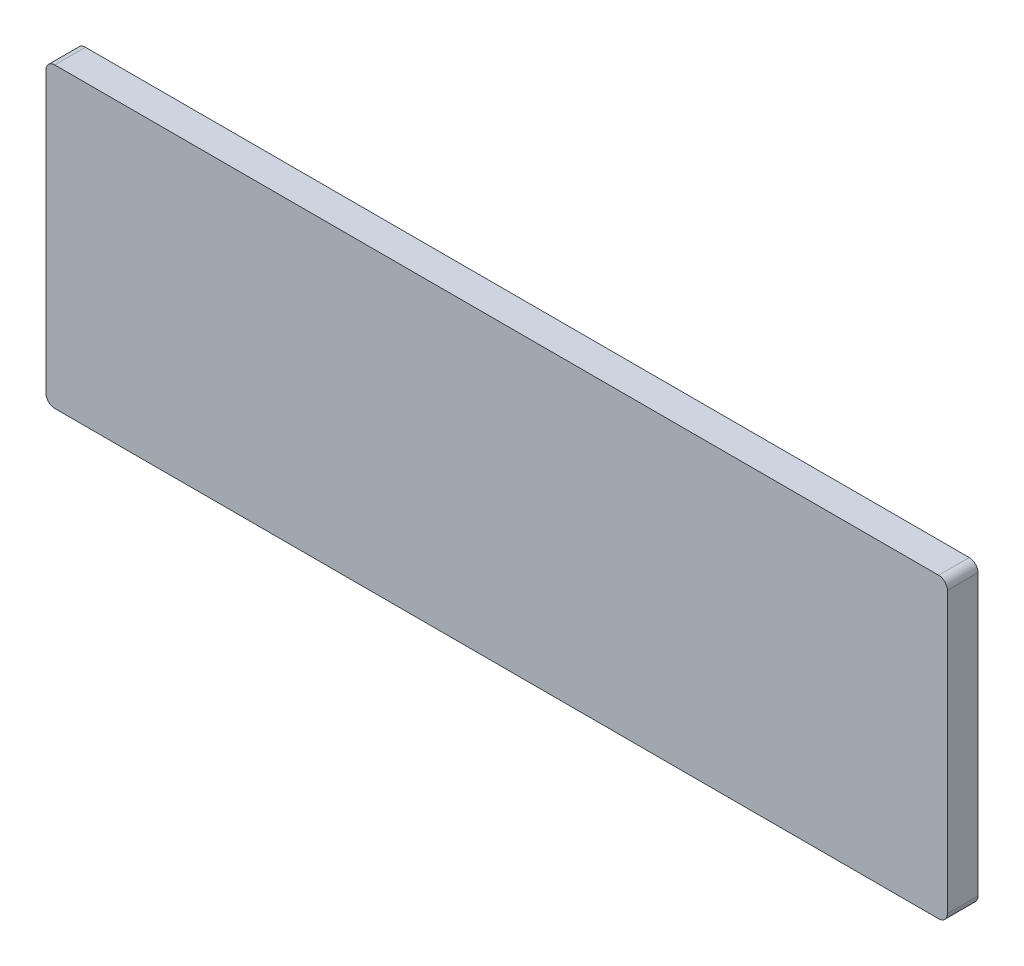
SolidWorks part; units mm, degrees
material "自定义塑料"
ref_plane "前视基准面" through (0, 0, 0) normal (0, 0, 1) x (1, 0, 0)
ref_plane "上视基准面" through (0, 0, 0) normal (0, 1, 0) x (1, 0, 0)
ref_plane "右视基准面" through (0, 0, 0) normal (1, 0, 0) x (0, 0, -1)
sketch "草图1" plane through (0, 0, 0) normal (0, 0, 1) x (1, 0, 0)
  line L0 (-103, 34) -> (103, -34) construction
  line L1 (-101, 34) -> (101, 34)
  line L2 (-103, 32) -> (-103, -32)
  line L3 (-101, -34) -> (101, -34)
  line L4 (103, 32) -> (103, -32)
  line L5 (103, 34) -> (-103, -34) construction
  arc A0 (101, -34) -> (103, -32) centre (101, -32) ccw
  arc A1 (101, 34) -> (103, 32) centre (101, 32) cw
  arc A2 (-103, -32) -> (-101, -34) centre (-101, -32) ccw
  arc A3 (-101, 34) -> (-103, 32) centre (-101, 32) ccw
  point P4 (0, 0)
  dimension "D3" = 2
  dimension "D1" = 206
  dimension "D2" = 68
extrude "凸台-拉伸1" add sketch "草图1" along normal blind 7
